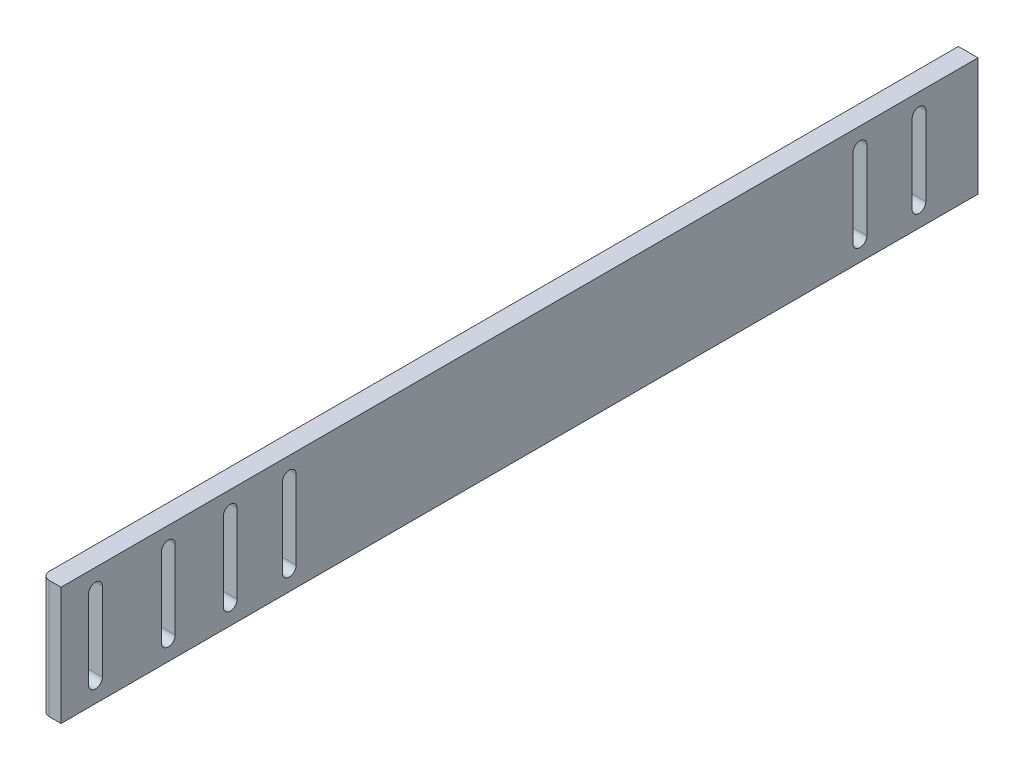
SolidWorks part; units mm, degrees
ref_plane "前视基准面" through (0, 0, 0) normal (0, 0, 1) x (1, 0, 0)
ref_plane "上视基准面" through (0, 0, 0) normal (0, 1, 0) x (1, 0, 0)
ref_plane "右视基准面" through (0, 0, 0) normal (1, 0, 0) x (0, 0, -1)
sketch "草图1" plane through (0, 0, 0) normal (1, 0, 0) x (0, 0, -1)
  line L0 (0, 0) -> (224.25, 0) construction
  line L1 (-1.75, 10) -> (1.75, 10)
  line L2 (-1.75, 10) -> (-1.75, -10)
  line L3 (-1.75, -10) -> (1.75, -10)
  line L4 (1.75, 10) -> (1.75, -10)
  line L5 (-1.75, 10) -> (1.75, -10) construction
  line L6 (-1.75, -10) -> (1.75, 10) construction
  line L7 (-5.75, -15) -> (5.75, -15)
  line L8 (-5.75, -15) -> (-5.75, 15)
  line L9 (-5.75, 15) -> (5.75, 15)
  line L10 (5.75, -15) -> (5.75, 15)
  line L11 (-5.75, -15) -> (5.75, 15) construction
  line L12 (-5.75, 15) -> (5.75, -15) construction
  line L13 (5.75, -15) -> (24.25, -15)
  line L14 (24.25, -15) -> (24.25, 15)
  line L15 (24.25, 15) -> (5.75, 15)
  line L16 (24.25, 15) -> (224.25, 15)
  line L17 (16.75, -10) -> (20.25, -10)
  line L18 (16.75, -10) -> (16.75, 10)
  line L19 (16.75, 10) -> (20.25, 10)
  line L20 (20.25, -10) -> (20.25, 10)
  line L21 (16.75, -10) -> (20.25, 10) construction
  line L22 (16.75, 10) -> (20.25, -10) construction
  line L23 (224.25, 15) -> (224.25, -15)
  line L24 (224.25, -15) -> (24.25, -15)
  line L25 (-5.75, 15) -> (-8.75, 15)
  line L26 (211, 10) -> (207.5, 10)
  line L27 (211, 10) -> (211, -10)
  line L28 (211, -10) -> (207.5, -10)
  line L29 (207.5, 10) -> (207.5, -10)
  line L30 (211, 10) -> (207.5, -10) construction
  line L31 (211, -10) -> (207.5, 10) construction
  line L32 (32.5, -10) -> (36, -10)
  line L33 (32.5, -10) -> (32.5, 10)
  line L34 (32.5, 10) -> (36, 10)
  line L35 (36, -10) -> (36, 10)
  line L36 (32.5, -10) -> (36, 10) construction
  line L37 (32.5, 10) -> (36, -10) construction
  line L38 (47.5, -10) -> (51, -10)
  line L39 (47.5, -10) -> (47.5, 10)
  line L40 (47.5, 10) -> (51, 10)
  line L41 (51, -10) -> (51, 10)
  line L42 (47.5, -10) -> (51, 10) construction
  line L43 (47.5, 10) -> (51, -10) construction
  line L44 (192.5, -10) -> (196, -10)
  line L45 (192.5, -10) -> (192.5, 10)
  line L46 (192.5, 10) -> (196, 10)
  line L47 (196, -10) -> (196, 10)
  line L48 (192.5, -10) -> (196, 10) construction
  line L49 (192.5, 10) -> (196, -10) construction
  line L50 (-8.75, 15) -> (-8.75, -15)
  line L51 (-8.75, -15) -> (-5.75, -15)
  circle A0 centre (0, 10) radius 1.75
  circle A1 centre (0, -10) radius 1.75
  circle A3 centre (18.5, 10) radius 1.75
  circle A4 centre (18.5, -10) radius 1.75
  circle A5 centre (209.25, 10) radius 1.75
  circle A6 centre (209.25, -10) radius 1.75
  circle A7 centre (34.25, 10) radius 1.75
  circle A8 centre (49.25, 10) radius 1.75
  circle A9 centre (49.25, -10) radius 1.75
  circle A10 centre (34.25, -10) radius 1.75
  circle A11 centre (194.25, 10) radius 1.75
  circle A12 centre (194.25, -10) radius 1.75
  point P0 (0, 0)
  point P10 (0, 0)
  point P18 (18.5, 0)
  point P28 (209.25, 0)
  point P39 (34.25, 0)
  point P44 (49.25, 0)
  point P57 (194.25, 0)
  dimension "D9" = 4
  dimension "D12" = 3.5
  dimension "D13" = 3.5
  dimension "D1" = 3.5
  dimension "D2" = 20
  dimension "D3" = 30
  dimension "D4" = 11.5
  dimension "D5" = 200
  dimension "D6" = 18.5
  dimension "D7" = 20
  dimension "D8" = 3.5
  dimension "D10" = 200
  dimension "D11" = 15
  dimension "D14" = 20
  dimension "D15" = 3.5
  dimension "D16" = 3.5
  dimension "D17" = 20
  dimension "D18" = 20
  dimension "D19" = 10
  dimension "D20" = 15
  dimension "D21" = 20
  dimension "D22" = 3.5
  dimension "D23" = 15
  dimension "D24" = 3
extrude "凸台-拉伸3" add sketch "草图1" along normal blind 5 contours L7 L10 L9 L8 A1 L2 A0 L4 | L14 L15 L10 L13 A4 L18 A3 L20 | L24 L23 L16 L14 A6 L29 A5 L27 | L50 L51 L8 L25
fillet "圆角2" radius 2 1 edges at (0, 0, 8.75)
